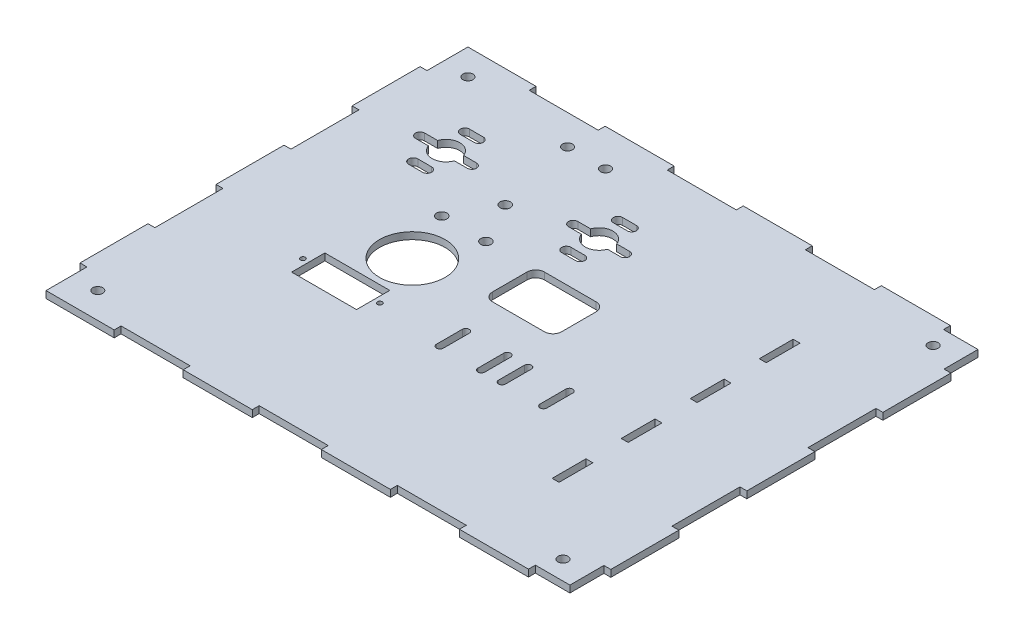
SolidWorks part; units mm, degrees
ref_plane "Front Plane" through (0, 0, 0) normal (0, 0, 1) x (1, 0, 0)
ref_plane "Top Plane" through (0, 0, 0) normal (0, 1, 0) x (1, 0, 0)
ref_plane "Right Plane" through (0, 0, 0) normal (1, 0, 0) x (0, 0, -1)
sketch "Sketch1" plane through (0, 0, 0) normal (0, 1, 0) x (1, 0, 0)
  line L1 (-44.45, 25.4) -> (44.45, 25.4)
  line L2 (-44.45, 25.4) -> (-44.45, -58.7223)
  line L3 (-44.45, -58.7223) -> (44.45, -58.7223)
  line L4 (44.45, 25.4) -> (44.45, -58.7223)
  point P5 (0, 25.4)
  dimension "D1" = 88.9
  dimension "D2" = 25.4
  dimension "D3" = 84.1223
extrude "Boss-Extrude1" add sketch "Sketch1" along normal blind 2.54
sketch "Sketch2" plane through (0, 2.54, 0) normal (0, 1, 0) x (1, 0, 0)
  line L0 (-25.6149, 17.35) -> (-30.6949, 17.35) construction
  line L1 (-25.6149, 15.65) -> (-30.6949, 15.65)
  line L2 (-25.6149, 19.05) -> (-30.6949, 19.05)
  line L3 (-30.6949, -1.65) -> (-25.6149, -1.65) construction
  line L4 (-30.6949, 0.05) -> (-25.6149, 0.05)
  line L5 (-30.6949, -3.35) -> (-25.6149, -3.35)
  line L6 (-37.6799, 7.85) -> (-18.6299, 7.85) construction
  line L7 (-37.6799, 9.55) -> (-18.6299, 9.55)
  line L8 (-37.6799, 6.15) -> (-18.6299, 6.15)
  line L9 (44.45, 25.4) -> (-44.45, 25.4) construction
  circle A0 centre (-28.1549, 7.85) radius 5.08
  arc A1 (-25.6149, 15.65) -> (-25.6149, 19.05) centre (-25.6149, 17.35) ccw
  arc A2 (-30.6949, 19.05) -> (-30.6949, 15.65) centre (-30.6949, 17.35) ccw
  arc A3 (-30.6949, 0.05) -> (-30.6949, -3.35) centre (-30.6949, -1.65) ccw
  arc A4 (-25.6149, -3.35) -> (-25.6149, 0.05) centre (-25.6149, -1.65) ccw
  arc A5 (-37.6799, 9.55) -> (-37.6799, 6.15) centre (-37.6799, 7.85) ccw
  arc A6 (-18.6299, 6.15) -> (-18.6299, 9.55) centre (-18.6299, 7.85) ccw
  point P1 (-28.1549, -1.65)
  point P8 (-28.1549, 17.35)
  point P18 (-28.1549, 7.85)
  dimension "D1" = 10.16
  dimension "D2" = 3.4
  dimension "D3" = 5.08
  dimension "D4" = 3.4
  dimension "D5" = 3.4
  dimension "D6" = 19
  dimension "D7" = 19.05
  dimension "D8" = 9.5
  dimension "D9" = 6.35
  dimension "D10" = 28.1549
extrude "Cut-Extrude1" cut sketch "Sketch2" against normal blind 2.54 contours L8 A0 | L7 A5 L8 A0 | L7 A0 | L8 A6 L7 A0 | L5 A4 L4 A3 | L2 A2 L1 A1
mirror "Mirror1" about plane through (0, 0, 0) normal (1, 0, 0) of "Cut-Extrude1"
sketch "Sketch3" plane through (0, 2.54, 0) normal (0, 1, 0) x (1, 0, 0)
  circle A0 centre (0, -32.6884) radius 12.065
  arc A1 (-18.6299, 6.15) -> (-18.6299, 9.55) centre (-18.6299, 7.85) ccw construction
  point P7 (-16.9299, 7.85)
  dimension "D2" = 24.13
  dimension "D1" = 40.5384
extrude "Cut-Extrude2" cut sketch "Sketch3" against normal through all
sketch "Sketch4" plane through (0, 2.54, 0) normal (0, 1, 0) x (1, 0, 0)
  line L0 (-44.45, -58.7223) -> (44.45, -58.7223) construction
  line L1 (6.0198, -58.7223) -> (-17.8562, -58.7223)
  line L2 (6.0198, -58.7223) -> (6.0198, -47.0129)
  line L3 (6.0198, -47.0129) -> (-17.8562, -47.0129)
  line L4 (-17.8562, -58.7223) -> (-17.8562, -47.0129)
  circle A0 centre (-20.0787, -52.8676) radius 0.889
  circle A1 centre (8.2423, -52.8676) radius 0.889
  point P11 (6.0198, -52.8676)
  dimension "D4" = 1.778
  dimension "D1" = 6.0198
  dimension "D2" = 23.876
  dimension "D3" = 11.7094
  dimension "D5" = 28.321
  dimension "D6" = 2.2225
extrude "Cut-Extrude3" cut sketch "Sketch4" against normal through all
hole_wizard "#6 Clearance Hole1" positions "Sketch6" profile "Sketch8" hole size "#6" standard "ANSI Inch" end condition through all
sketch "Sketch6" plane through (0, 2.54, 0) normal (0, 1, 0) x (1, 0, 0)
  line L0 (44.45, 25.4) -> (-44.45, 25.4) construction
  line L1 (0, 0) -> (0, -17.2298) construction
  point P0 (0, 1.4986)
  point P2 (-8.128, -13.7414)
  point P4 (8.128, -13.7414)
  dimension "D1" = 23.9014
  dimension "D2" = 16.256
  dimension "D3" = 15.24
sketch "Sketch8" plane through (0, 2.54, -1.4986) normal (1, 0, 0) x (0, 0, 1)
  line L0 (0, 0) -> (0, 2.54)
  line L1 (0, 2.54) -> (1.8986, 2.54)
  line L2 (1.8986, 2.54) -> (1.8986, 0)
  line L5 (1.8986, 0) -> (0, 0)
  line L11 (0, -6.35) -> (0, 107.95) construction
  dimension "Thru Hole Dia." = 3.7973
  dimension "Thru Hole Depth" = 2.54
sketch "Sketch9" plane through (0, 0, 0) normal (0, 1, 0) x (1, 0, 0)
  line L1 (-44.45, 25.4) -> (44.45, 25.4)
  line L5 (6.0198, -58.7223) -> (6.0198, -59.2303)
  line L6 (6.0198, -59.2303) -> (-17.8562, -59.2303)
  line L7 (-17.8562, -58.7223) -> (-17.8562, -59.2303)
  line L8 (-44.45, -58.7223) -> (-17.8562, -58.7223) construction
  line L13 (-44.45, -58.7223) -> (-17.8562, -58.7223)
  line L15 (-44.45, 25.4) -> (-44.45, 42.3697)
  line L16 (-44.45, 42.3697) -> (133.0223, 42.3697)
  line L17 (133.0223, 42.3697) -> (133.0223, -107.7443)
  line L19 (44.45, 25.4) -> (44.45, -58.7223)
  line L20 (-44.45, -58.7223) -> (-44.45, -107.7443)
  line L21 (-44.45, -107.7443) -> (133.0223, -107.7443)
  line L22 (6.0198, -58.7223) -> (44.45, -58.7223)
  dimension "D1" = 16.9697
  dimension "D2" = 0.508
  dimension "D3" = 177.4723
  dimension "D4" = 49.022
extrude "Boss-Extrude2" add sketch "Sketch9" along normal blind 2.54
sketch "Sketch10" plane through (0, 2.54, 0) normal (0, 1, 0) x (1, 0, 0)
  line L1 (95.7605, 11.6357) -> (98.3005, 11.6357)
  line L2 (95.7605, 11.6357) -> (95.7605, -0.8103)
  line L3 (95.7605, -0.8103) -> (98.3005, -0.8103)
  line L4 (98.3005, 11.6357) -> (98.3005, -0.8103)
  line L13 (133.0223, 42.3697) -> (-44.45, 42.3697) construction
  line L14 (133.0223, -107.7443) -> (133.0223, 42.3697) construction
  point P4 (97.0305, 11.6357)
  dimension "D1" = 35.9918
  dimension "D2" = 2.54
  dimension "D3" = 12.446
  dimension "D4" = 30.734
extrude "Cut-Extrude4" cut sketch "Sketch10" against normal through all
pattern_linear "LPattern1" count 4 spacing 25.4 along (0, 0, 1) of "Cut-Extrude4"
sketch "Sketch11" plane through (0, 2.54, 0) normal (0, 1, 0) x (1, 0, 0)
  line L0 (-44.45, -107.7443) -> (133.0223, -107.7443) construction
  line L1 (94.9223, -107.7443) -> (120.3223, -107.7443)
  line L2 (94.9223, -107.7443) -> (94.9223, -110.2843)
  line L3 (94.9223, -110.2843) -> (120.3223, -110.2843)
  line L4 (120.3223, -107.7443) -> (120.3223, -110.2843)
  line L6 (133.0223, -107.7443) -> (133.0223, 42.3697) construction
  dimension "D1" = 25.4
  dimension "D2" = 2.54
  dimension "D3" = 12.7
extrude "Boss-Extrude3" add sketch "Sketch11" against normal blind 2.54
pattern_linear "LPattern2" count 4 spacing 50.8 along (-1, 0, 0) count 2 spacing 152.654 along (0, 0, -1) of "Boss-Extrude3"
sketch "Sketch12" plane through (0, 2.54, 0) normal (0, 1, 0) x (1, 0, 0)
  line L0 (133.0223, -107.7443) -> (133.0223, 42.3697) construction
  line L1 (133.0223, -95.2348) -> (135.5623, -95.2348)
  line L2 (133.0223, -95.2348) -> (133.0223, -70.2158)
  line L3 (133.0223, -70.2158) -> (135.5623, -70.2158)
  line L4 (135.5623, -95.2348) -> (135.5623, -70.2158)
  line L5 (120.3223, -107.7443) -> (133.0223, -107.7443) construction
  dimension "D1" = 12.5095
  dimension "D2" = 25.019
  dimension "D3" = 2.54
extrude "Boss-Extrude4" add sketch "Sketch12" against normal blind 2.54
pattern_linear "LPattern3" count 3 spacing 50.038 along (0, 0, -1) of "Boss-Extrude4"
sketch "Sketch13" plane through (0, 2.54, 0) normal (0, 1, 0) x (1, 0, 0)
  line L1 (-44.45, -110.2843) -> (-57.4777, -110.2843)
  line L2 (-44.45, -110.2843) -> (-44.45, 44.9097)
  line L3 (-44.45, 44.9097) -> (-57.4777, 44.9097)
  line L4 (-57.4777, -110.2843) -> (-57.4777, 44.9097)
  line L5 (-44.45, 42.3697) -> (-44.45, -107.7443) construction
  line L6 (-57.4777, -110.2843) -> (-32.0777, -110.2843) construction
extrude "Cut-Extrude5" cut sketch "Sketch13" against normal through all
hole_wizard "#6 Clearance Hole2" positions "Sketch15" profile "Sketch16" hole size "#6" standard "ANSI Inch" end condition up to next
sketch "Sketch15" plane through (0, 0, 0) normal (0, -1, 0) x (-1, 0, 0)
  point P0 (6.9901, 31.39)
  point P2 (-6.9799, 31.39)
  dimension "D1" = 6.9799
  dimension "D2" = 31.39
  dimension "D3" = 13.97
sketch "Sketch16" plane through (-6.9901, 0, -31.39) normal (1, 0, 0) x (0, 0, -1)
  line L0 (0, 0) -> (0, 2.54)
  line L1 (0, 2.54) -> (1.8288, 2.54)
  line L2 (1.8288, 2.54) -> (1.8288, 0)
  line L5 (1.8288, 0) -> (0, 0)
  line L11 (0, -6.35) -> (0, 107.95) construction
  dimension "Thru Hole Dia." = 3.6576
  dimension "Thru Hole Depth" = 2.54
sketch "Sketch17" plane through (0, 2.54, 0) normal (0, 1, 0) x (1, 0, 0)
  line L0 (-44.45, -110.2843) -> (-32.0777, -110.2843) construction
  line L1 (-44.45, 44.9097) -> (-57.15, 44.9097)
  line L2 (-44.45, 44.9097) -> (-44.45, -110.2843)
  line L3 (-44.45, -110.2843) -> (-57.15, -110.2843)
  line L4 (-57.15, 44.9097) -> (-57.15, -110.2843)
  dimension "D1" = 12.7
extrude "Boss-Extrude5" add sketch "Sketch17" against normal blind 2.54
pattern_linear "LPattern4" count 2 spacing 192.7123 along (-1, 0, 0) of "LPattern3", "Boss-Extrude4"
sketch "Sketch18" plane through (0, 2.54, 0) normal (0, 1, 0) x (1, 0, 0)
  line L1 (25.4, -12.7) -> (50.8, -12.7)
  line L2 (25.4, -12.7) -> (25.4, -31.75)
  line L3 (25.4, -31.75) -> (50.8, -31.75)
  line L4 (50.8, -12.7) -> (50.8, -31.75)
  dimension "D1" = 19.05
  dimension "D2" = 25.4
  dimension "D3" = 25.4
  dimension "D4" = 12.7
extrude "Cut-Extrude6" cut sketch "Sketch18" against normal through all
fillet "Fillet1" radius 3.175 4 edges at (25.4, 1.27, 31.75) (50.8, 1.27, 31.75) (50.8, 1.27, 12.7) (25.4, 1.27, 12.7)
sketch "Sketch19" plane through (0, 2.54, 0) normal (0, 1, 0) x (1, 0, 0)
  line L0 (33.02, -46.0375) -> (33.02, -55.5625) construction
  line L1 (34.29, -46.0375) -> (34.29, -55.5625)
  line L2 (31.75, -46.0375) -> (31.75, -55.5625)
  arc A0 (34.29, -46.0375) -> (31.75, -46.0375) centre (33.02, -46.0375) ccw
  arc A1 (31.75, -55.5625) -> (34.29, -55.5625) centre (33.02, -55.5625) ccw
  point P2 (33.02, -50.8)
  point P7 (0, 0)
  dimension "D1" = 2.54
  dimension "D2" = 9.525
  dimension "D3" = 50.8
  dimension "D4" = 33.02
extrude "Cut-Extrude7" cut sketch "Sketch19" against normal blind 2.54
pattern_linear "LPattern5" count 6 spacing 7.62 along (1, 0, 0) skipping (1, 0), (4, 0) of "Cut-Extrude7"
hole_wizard "#6 Clearance Hole3" positions "Sketch20" profile "Sketch21" hole size "#6" standard "ANSI Inch"
sketch "Sketch20" plane through (0, 2.54, 0) normal (0, 1, 0) x (1, 0, 0)
  line L0 (-57.15, 44.9097) -> (-57.15, 29.8602) construction
  line L1 (-32.0777, 44.9097) -> (-57.15, 44.9097) construction
  line L2 (133.0223, 29.8602) -> (133.0223, 42.3697) construction
  line L3 (-57.15, -110.2843) -> (-32.0777, -110.2843) construction
  point P0 (-47.625, 35.3847)
  point P2 (-47.625, -100.7593)
  point P4 (123.4973, -100.7593)
  point P6 (123.4973, 35.3847)
  point P15 (0, 0)
  point P16 (0, 0)
  point P17 (0, 0)
  point P18 (0, 0)
  dimension "D1" = 9.525
  dimension "D2" = 9.525
  dimension "D3" = 9.525
  dimension "D4" = 9.525
sketch "Sketch21" plane through (-47.625, 2.54, -35.3847) normal (1, 0, 0) x (0, 0, 1)
  line L0 (0, 0) -> (0, 10.4969)
  line L1 (0, 10.4969) -> (1.8288, 9.398)
  line L2 (1.8288, 9.398) -> (1.8288, 0)
  line L5 (1.8288, 0) -> (0, 0)
  line L10 (0, 10.4969) -> (-1.8288, 9.398) construction
  line L11 (0, -6.35) -> (0, 107.95) construction
  dimension "Hole Dia." = 3.6576
  dimension "Hole Depth" = 9.398
  dimension "Drill Angle" = 118
